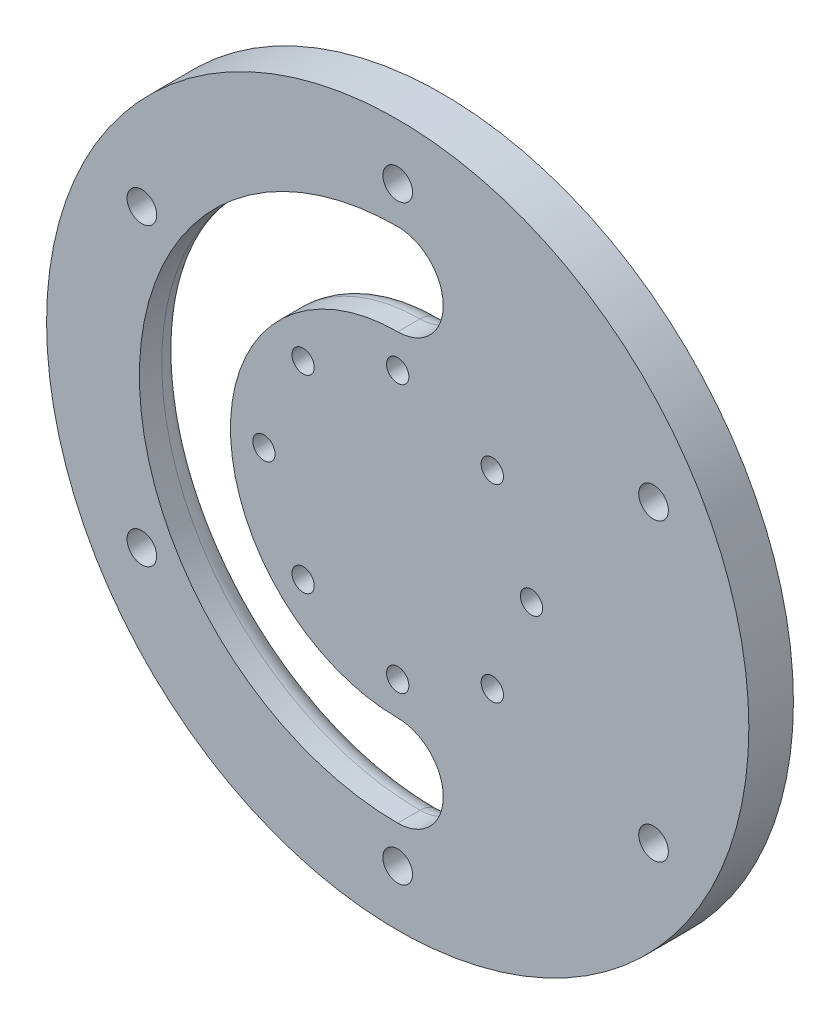
SolidWorks part; units mm, degrees
material "Nylon PA 12"
ref_plane "Front Plane" through (0, 0, 0) normal (0, 0, 1) x (1, 0, 0)
ref_plane "Top Plane" through (0, 0, 0) normal (0, 1, 0) x (1, 0, 0)
ref_plane "Right Plane" through (0, 0, 0) normal (1, 0, 0) x (0, 0, -1)
sketch "Sketch1" plane through (0, 0, 0) normal (0, 0, 1) x (1, 0, 0)
  line L0 (0, 8.25) -> (0, -8.25) construction
  line L1 (-8.25, 0) -> (8.25, 0) construction
  circle A0 centre (0, 8.25) radius 1.33 construction
  circle A1 centre (8.25, 0) radius 1.33 construction
  circle A2 centre (0, -8.25) radius 1.33 construction
  circle A3 centre (-8.25, 0) radius 1.33 construction
  circle A5 centre (0, 0) radius 31.5
  point P5 (0, 0)
  point P6 (0, 0)
  dimension "D1" = 4
extrude "Elbow Plate" add sketch "Sketch1" along normal blind 4
sketch "Sketch2" plane through (0, 0, 0) normal (0, 0, -1) x (-1, 0, 0)
  line L0 (8.25, 0) -> (-8.25, 0) construction
  circle A0 centre (0, 0) radius 12 construction
  circle A1 centre (0, 12) radius 1
  circle A2 centre (8.4853, 8.4853) radius 1
  circle A3 centre (12, 0) radius 1
  circle A4 centre (8.4853, -8.4853) radius 1
  circle A5 centre (0, -12) radius 1
  circle A6 centre (-8.4853, -8.4853) radius 1
  circle A7 centre (-12, 0) radius 1
  circle A8 centre (-8.4853, 8.4853) radius 1
  dimension "D2" = 2
  dimension "D3" = 24
  dimension "D1" = 8
sketch "Sketch3" plane through (0, 0, 0) normal (0, 0, -1) x (-1, 0, 0)
  line L0 (8.25, 0) -> (-8.25, 0) construction
  circle A0 centre (0, 0) radius 26.5 construction
  circle A1 centre (0, 0) radius 31.5 construction
  circle A8 centre (22.9497, 13.25) radius 1.33
  circle A9 centre (0, 26.5) radius 1.33
  circle A15 centre (22.9497, -13.25) radius 1.33
  circle A16 centre (0, -26.5) radius 1.33
  circle A17 centre (-22.9497, -13.25) radius 1.33
  circle A18 centre (-22.9497, 13.25) radius 1.33
  dimension "D1" = 5
  dimension "D2" = 6
  dimension "D3" = 53
  dimension "D4" = 2.66
extrude "Screw Holes" cut sketch "Sketch3" against normal through all
sketch "Sketch4" plane through (0, 0, 4) normal (0, 0, 1) x (1, 0, 0)
  line L0 (0, 0) -> (15.3714, -15.3714) construction
  line L1 (-8.25, 0) -> (8.25, 0) construction
  line L2 (0, 0) -> (16.7612, 16.7612) construction
  line L3 (0, -8.25) -> (0, -33.1782) construction
  line L4 (0, 8.25) -> (0, 26.5) construction
  arc A1 (0, -23.1723) -> (0, -15) centre (0, -19.0862) ccw
  arc A2 (0, 15) -> (0, 23.1723) centre (0, 19.0862) ccw
  arc A3 (0, 19.0862) -> (4.0627, -18.6488) centre (0, 0) ccw construction
  arc A4 (0, 15) -> (0, -15) centre (0, 0) ccw
  arc A5 (0, 23.1723) -> (0, -23.1723) centre (0, 0) ccw
  dimension "D4" = 15
  dimension "D5" = 23.1723
  dimension "D1" = 270
  dimension "D2" = 45
extrude "Cable Slot" cut sketch "Sketch4" against normal blind 4
fillet "Fillet1" radius 2 4 edges at (4.0862, 19.0862, 0) (-15, 0, 0) (4.0862, -19.0862, 0) (-23.1723, 0, 0)
hole_wizard "CBORE for M6 Hex Head Bolt1" positions "3DSketch1" profile "Sketch5" counterbore size "M6" standard "ANSI Metric" end condition through all
sketch3d "3DSketch1"
  point P0 (12, 0, 0)
  point P3 (8.4853, 8.4853, 0)
  point P6 (0, 12, 0)
  point P9 (-8.4853, 8.4853, 0)
  point P12 (-12, 0, 0)
  point P15 (-8.4853, -8.4853, 0)
  point P18 (0, -12, 0)
  point P21 (8.4853, -8.4853, 0)
sketch "Sketch5" plane through (12, 0, 0) normal (1, 0, 0) x (0, 1, 0)
  line L0 (0, 0) -> (0, 4)
  line L1 (0, 4) -> (1, 4)
  line L3 (1, 4) -> (1, 1)
  line L4 (1, 1) -> (1.75, 1)
  line L5 (1.75, 1) -> (1.75, 0)
  line L7 (1.75, 0) -> (0, 0)
  line L11 (0, -6.35) -> (0, 107.95) construction
  dimension "Thru Hole Dia." = 2
  dimension "Thru Hole Depth" = 4
  dimension "C'Bore Dia." = 3.5
  dimension "C'Bore Depth" = 1
